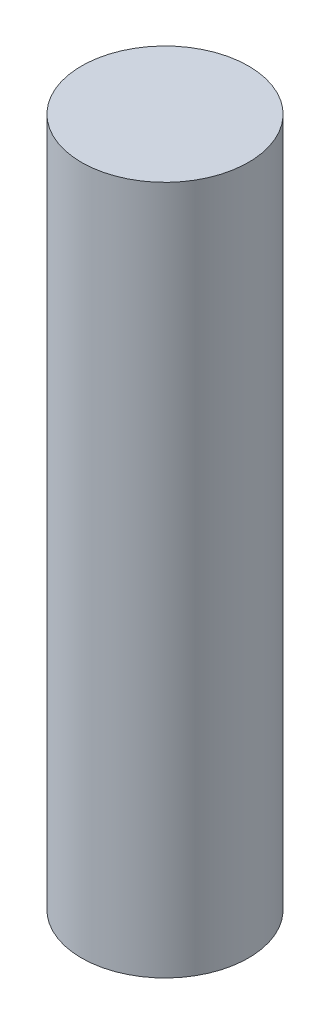
SolidWorks part; units mm, degrees
ref_plane "Front Plane" through (0, 0, 0) normal (0, 0, 1) x (1, 0, 0)
ref_plane "Top Plane" through (0, 0, 0) normal (0, 1, 0) x (1, 0, 0)
ref_plane "Right Plane" through (0, 0, 0) normal (1, 0, 0) x (0, 0, -1)
sketch "Sketch1" plane through (0, 0, 0) normal (1, 0, 0) x (0, 0, -1)
  line L0 (0, 6.4889) -> (0, -3.1111) construction
  line L1 (4, 30.6444) -> (4, -2.3556)
  line L2 (4, -2.3556) -> (0, -2.3556)
  line L3 (4, 30.6444) -> (0, 30.6444)
  line L4 (0, 30.6444) -> (0, -2.3556)
  dimension "D1" = 4
  dimension "D2" = 33
revolve "Revolve1" add sketch "Sketch1" angle 360 about L0
